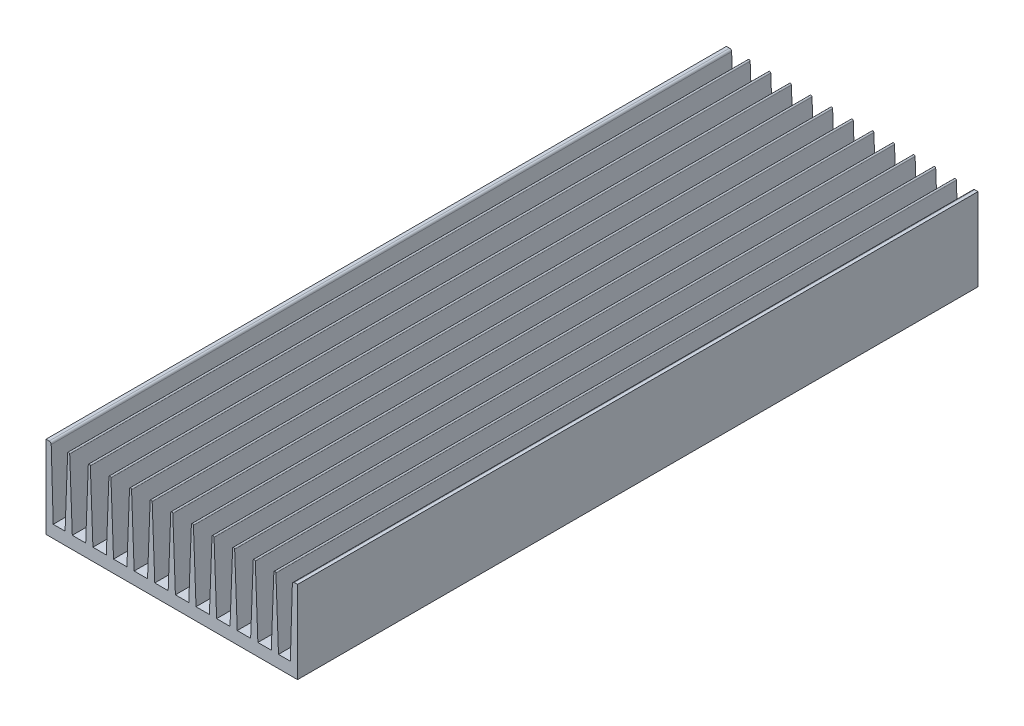
SolidWorks part; units mm, degrees
ref_plane "Спереди" through (0, 0, 0) normal (0, 0, 1) x (1, 0, 0)
ref_plane "Сверху" through (0, 0, 0) normal (0, 1, 0) x (1, 0, 0)
ref_plane "Справа" through (0, 0, 0) normal (1, 0, 0) x (0, 0, -1)
sketch "Эскиз1" plane through (0, 0, 0) normal (0, 0, 1) x (1, 0, 0)
  line L0 (0, 40) -> (1.529, 40)
  line L1 (0, 0) -> (122, 0)
  line L2 (2.5285, 39.0294) -> (3.5, 6)
  line L3 (0, 40) -> (0, 0)
  line L4 (122, 40) -> (122, 0)
  line L5 (61, 63.7127) -> (61, -22.2582) construction
  line L8 (122, 40) -> (120.471, 40)
  line L9 (119.4715, 39.0294) -> (118.5, 6)
  line L10 (3.5, 6) -> (118.5, 6)
  arc A0 (1.529, 40) -> (2.5285, 39.0294) centre (1.529, 39) cw
  arc A2 (120.471, 40) -> (119.4715, 39.0294) centre (120.471, 39) ccw
  point P18 (119.5, 40)
  dimension "D9" = 1
  dimension "D1" = 122
  dimension "D2" = 6
  dimension "D3" = 40
  dimension "D4" = 3.5
  dimension "D7" = 2.5
extrude "Вытянуть1" add sketch "Эскиз1" along normal blind 330
sketch "Эскиз2" plane through (0, 0, 330) normal (0, 0, 1) x (1, 0, 0)
  line L0 (118.5, 6) -> (3.5, 6) construction
  line L1 (10.5, 39.5) -> (9.25, 6)
  line L2 (11, 39.5) -> (11, 22.5548) construction
  line L3 (11.5, 39.5) -> (12.75, 6)
  line L4 (9.25, 6) -> (12.75, 6)
  line L6 (0, 40) -> (0, 0) construction
  arc A0 (10.5, 39.5) -> (11.5, 39.5) centre (11, 39.5) cw
  dimension "D1" = 34
  dimension "D3" = 0.5
  dimension "D2" = 3.5
  dimension "D4" = 11
  dimension "D5" = 1
extrude "Вытянуть3" add sketch "Эскиз2" against normal blind 330
pattern_curve "Кривая1" of "Вытянуть3" along edge at (61, 0, 0) parameters "D1"=11, "D3"=10, "D2"=1, "D4"=50
sketch "Эскиз3" plane through (0, 0, 0) normal (0, -1, 0) x (1, 0, 0)
  line L0 (-14.0506, 322) -> (137.5079, 322) construction
  line L1 (0, 330) -> (122, 330) construction
  line L3 (-46.7511, 165) -> (151.4312, 165) construction
  line L4 (0, 0) -> (122, 0) construction
  line L6 (0, 330) -> (0, 0) construction
  circle A0 centre (26, 322) radius 2.25
  circle A1 centre (96, 322) radius 2.25
  circle A2 centre (96, 8) radius 2.25
  circle A3 centre (26, 8) radius 2.25
  dimension "D2" = 70
  dimension "D4" = 4.5
  dimension "D1" = 8
  dimension "D3" = 26
extrude "Вырез-Вытянуть1" cut sketch "Эскиз3" against normal blind 6
sketch "Эскиз4" plane through (147.9336, 0, 237.9463) normal (0, -1, 0) x (-1, 0, 0)
  line L0 (85.9336, 76.9463) -> (85.9336, 211.9463) construction
  line L1 (80.9336, -66.7149) -> (80.9336, 39.2256) construction
  line L2 (25.9336, -92.0537) -> (25.9336, 237.9463) construction
  line L3 (147.9336, 237.9463) -> (25.9336, 237.9463) construction
  line L4 (147.9336, -92.0537) -> (147.9336, 237.9463) construction
  line L9 (147.9336, -92.0537) -> (25.9336, -92.0537) construction
  circle A0 centre (80.9336, -68.0537) radius 1.6
  circle A1 centre (42.4336, 124.3463) radius 1.6
  circle A2 centre (85.9336, 211.9463) radius 1.6
  circle A3 centre (85.9336, 76.9463) radius 1.6
  circle A7 centre (80.9336, 61.9463) radius 1.6
  circle A9 centre (118.9336, 46.4463) radius 1.6
  dimension "D3" = 130
  dimension "D5" = 135
  dimension "D6" = 3.2
  dimension "D7" = 47.4
  dimension "D8" = 43.5
  dimension "D10" = 29
  dimension "D13" = 24
  dimension "D2" = 60
  dimension "D4" = 26
  dimension "D9" = 55
extrude "Вырез-Вытянуть2" cut sketch "Эскиз4" against normal blind 6
cosmetic thread "Условное изображение резьбы5" parameters "D2"=4
cosmetic thread "Условное изображение резьбы7" parameters "D2"=4
cosmetic thread "Условное изображение резьбы12" parameters "D1"=6, "D2"=4
cosmetic thread "Условное изображение резьбы13" parameters "D1"=6, "D2"=4
cosmetic thread "Условное изображение резьбы15" parameters "D1"=6, "D2"=4
cosmetic thread "Условное изображение резьбы16" parameters "D1"=5, "D2"=4
